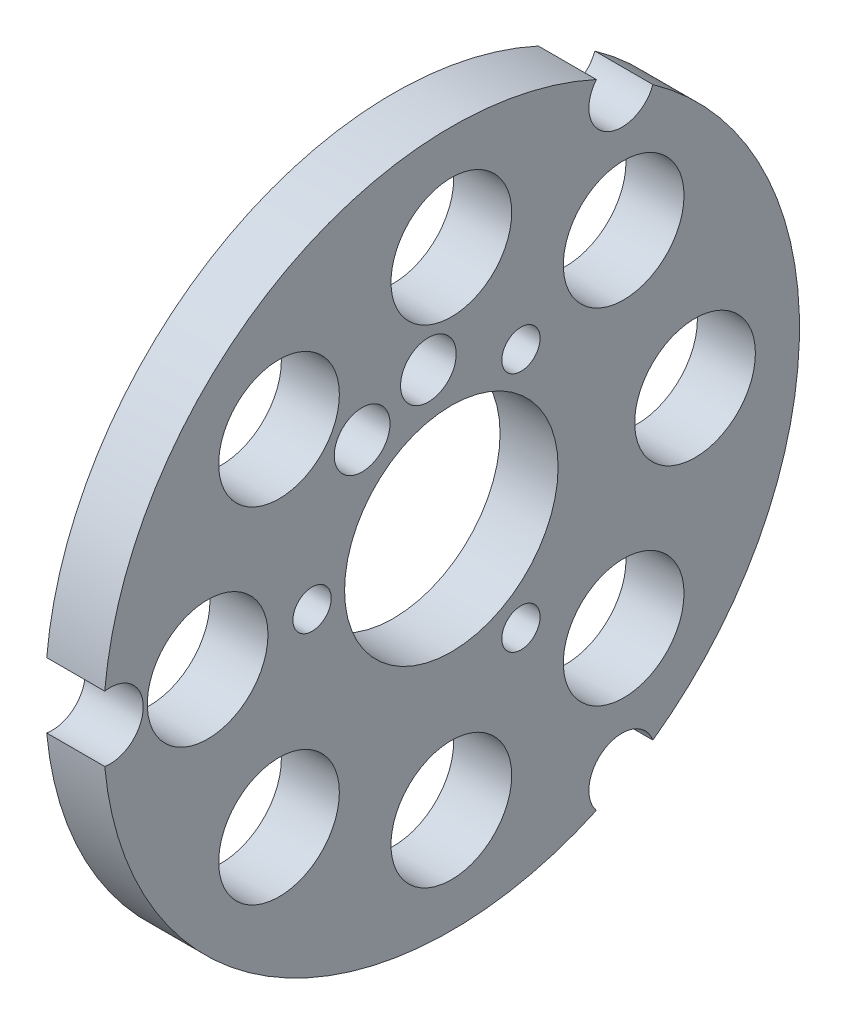
SolidWorks part; units mm, degrees
material "Alumina"
ref_plane "Front Plane" through (0, 0, 0) normal (0, 0, 1) x (1, 0, 0)
ref_plane "Top Plane" through (0, 0, 0) normal (0, 1, 0) x (1, 0, 0)
ref_plane "Right Plane" through (0, 0, 0) normal (1, 0, 0) x (0, 0, -1)
sketch "Axial profile (mm)" plane through (0, 0, 0) normal (0, 0, 1) x (1, 0, 0)
  line L0 (-110, 0) -> (75, 0) construction
  line L1 (143.7, 9.2) -> (148.7, 9.2)
  line L2 (148.7, 9.2) -> (148.7, 30)
  line L3 (148.7, 30) -> (143.7, 30)
  line L4 (143.7, 30) -> (143.7, 9.2)
revolve "Full revolution" add sketch "Axial profile (mm)" angle 360 about L0
sketch "Sketch2" plane through (0, 0, 0) normal (1, 0, 0) x (0, 0, -1)
  circle A0 centre (0, 21) radius 5.2
  circle A1 centre (-14.8492, 14.8492) radius 5.2
  circle A2 centre (-21, 0) radius 5.2
  circle A3 centre (-14.8492, -14.8492) radius 5.2
  circle A4 centre (0, -21) radius 5.2
  circle A5 centre (14.8492, -14.8492) radius 5.2
  circle A6 centre (21, 0) radius 5.2
  circle A7 centre (14.8492, 14.8492) radius 5.2
  circle A8 centre (-1.9774, 12.8487) radius 2.4
  circle A9 centre (-7.6872, 10.4836) radius 2.4
  circle A10 centre (-12, 0) radius 1.65
  circle A11 centre (6, -10.3923) radius 1.65
  circle A12 centre (6, 10.3923) radius 1.65
  circle A13 centre (-29.4, 0) radius 2.85
  circle A14 centre (14.7, -25.4611) radius 2.85
  circle A15 centre (14.7, 25.4611) radius 2.85
extrude "Axial holes" cut sketch "Sketch2" along normal through all and the other way through all
